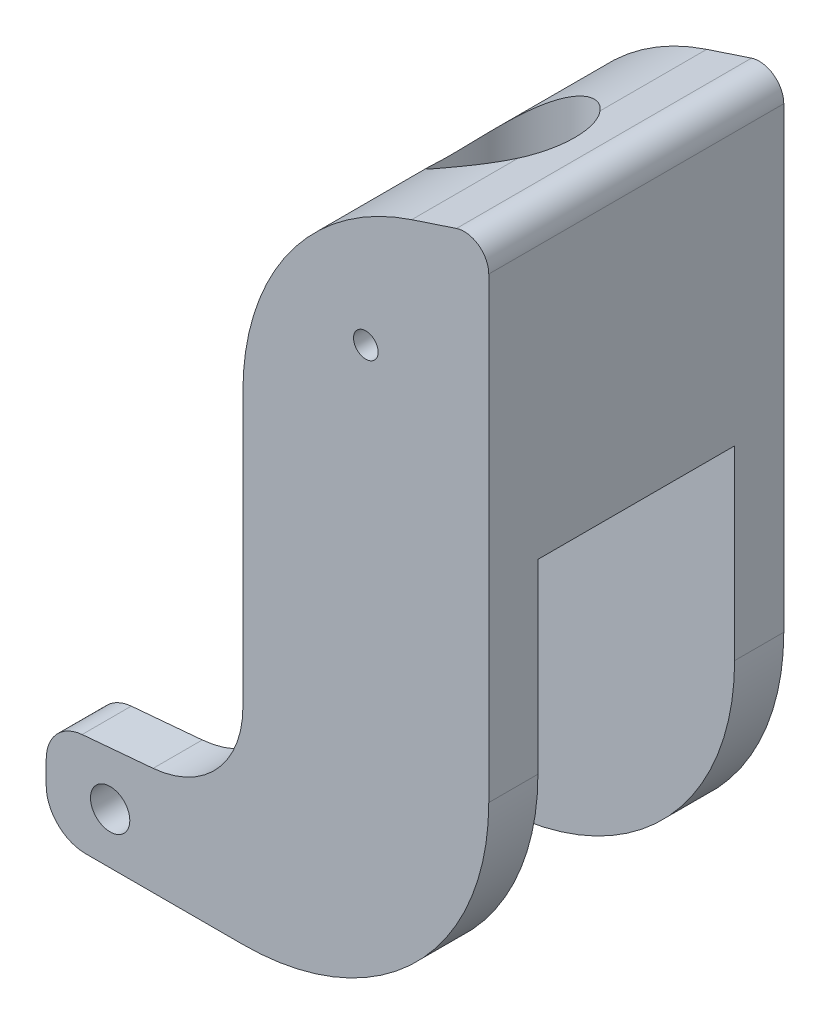
SolidWorks part; units mm, degrees
ref_plane "Front Plane" through (0, 0, 0) normal (0, 0, 1) x (1, 0, 0)
ref_plane "Top Plane" through (0, 0, 0) normal (0, 1, 0) x (1, 0, 0)
ref_plane "Right Plane" through (0, 0, 0) normal (1, 0, 0) x (0, 0, -1)
sketch "Sketch1" plane through (0, 0, 0) normal (0, 0, 1) x (1, 0, 0)
  line L0 (0, 18.3266) -> (0, 73.8482)
  line L1 (-18.2569, -1.5973) -> (-32.6972, -2.8606)
  line L2 (-40, -10.8302) -> (-40, -15.4995)
  line L3 (-32, -23.4995) -> (0, -23.4995)
  line L4 (50, 26.5005) -> (50, 119.5852)
  line L5 (43.4331, 124.3333) -> (34.3307, 121.3295)
  arc A0 (0, 73.8482) -> (34.3307, 121.3295) centre (50, 73.8482) cw
  arc A1 (0, -23.4995) -> (50, 26.5005) centre (0, 26.5005) ccw
  arc A2 (50, 119.5852) -> (43.4331, 124.3333) centre (45, 119.5852) ccw
  arc A3 (-32.6972, -2.8606) -> (-40, -10.8302) centre (-32, -10.8302) ccw
  arc A4 (-40, -15.4995) -> (-32, -23.4995) centre (-32, -15.4995) ccw
  arc A5 (0, 18.3266) -> (-18.2569, -1.5973) centre (-20, 18.3266) cw
  circle A6 centre (-27, -13.1649) radius 4
  point P9 (0, 110)
  point P12 (50, -23.4995)
  point P15 (50, 126.5005)
  point P18 (-40, -3.4995)
  point P21 (-40, -23.4995)
  point P24 (0, 0)
  point P27 (0, 0)
  point P28 (-40, -13.1649)
  dimension "D7" = 50
  dimension "D8" = 50
  dimension "D9" = 5
  dimension "D10" = 8
  dimension "D11" = 20
  dimension "D12" = 8
  dimension "D1" = 110
  dimension "D2" = 95
  dimension "D3" = 40
  dimension "D4" = 90
  dimension "D5" = 150
  dimension "D6" = 20
  dimension "D13" = 13
extrude "Boss-Extrude1" add sketch "Sketch1" along normal blind 60
sketch "Sketch2" plane through (0, 0, 0) normal (1, 0, 0) x (0, 0, -1)
  line L0 (-60, 124.3333) -> (0, 124.3333) construction
  line L1 (-10, -35.6667) -> (-50, -35.6667)
  line L2 (-10, -35.6667) -> (-10, 64.3333)
  line L3 (-10, 64.3333) -> (-50, 64.3333)
  line L4 (-50, -35.6667) -> (-50, 64.3333)
  line L5 (-10, -35.6667) -> (-50, 64.3333) construction
  line L6 (-10, 64.3333) -> (-50, -35.6667) construction
  line L7 (-60, 73.8482) -> (-60, 18.3266) construction
  line L8 (0, 73.8482) -> (0, 18.3266) construction
  point P0 (-30, 14.3333)
  point P5 (-30.3361, 21.4709)
  dimension "D1" = 60
  dimension "D2" = 10
  dimension "D3" = 10
  dimension "D4" = 100
extrude "Cut-Extrude1" cut sketch "Sketch2" against normal through all both and the other way through all
sketch "Sketch4" plane through (0, 0, 0) normal (0, 1, 0) x (1, 0, 0)
  line L0 (50, -60) -> (50, 0) construction
  line L1 (50, -60) -> (50, 0) construction
  circle A0 centre (25, -30) radius 12.5
  dimension "D2" = 25
  dimension "D1" = 25
  dimension "D3" = 30
extrude "Cut-Extrude2" cut sketch "Sketch4" against normal through all both and the other way through all
sketch "Sketch5" plane through (0, 0, 60) normal (0, 0, 1) x (1, 0, 0)
  line L6 (0, 73.8482) -> (0, 18.3266)
  line L7 (-18.2569, -1.5973) -> (-32.6972, -2.8606)
  line L8 (-40, -10.8302) -> (-40, -15.4995)
  line L9 (-32, -23.4995) -> (0, -23.4995)
  line L10 (50, 26.5005) -> (50, 119.5852)
  line L11 (43.4331, 124.3333) -> (34.3307, 121.3295)
  line L12 (0, 73.8482) -> (0, 18.3266) construction
  line L13 (-18.2569, -1.5973) -> (-32.6972, -2.8606) construction
  line L14 (-40, -10.8302) -> (-40, -15.4995) construction
  line L15 (-32, -23.4995) -> (0, -23.4995) construction
  line L16 (50, 26.5005) -> (50, 119.5852) construction
  line L17 (43.4331, 124.3333) -> (34.3307, 121.3295) construction
  circle A0 centre (25, 94.5852) radius 2.5
  arc A6 (34.3307, 121.3295) -> (0, 73.8482) centre (50, 73.8482) ccw
  arc A7 (-18.2569, -1.5973) -> (0, 18.3266) centre (-20, 18.3266) ccw
  arc A8 (-32.6972, -2.8606) -> (-40, -10.8302) centre (-32, -10.8302) ccw
  arc A9 (-40, -15.4995) -> (-32, -23.4995) centre (-32, -15.4995) ccw
  arc A10 (0, -23.4995) -> (50, 26.5005) centre (0, 26.5005) ccw
  arc A11 (50, 119.5852) -> (43.4331, 124.3333) centre (45, 119.5852) ccw
  arc A12 (34.3307, 121.3295) -> (0, 73.8482) centre (50, 73.8482) ccw construction
  arc A13 (-18.2569, -1.5973) -> (0, 18.3266) centre (-20, 18.3266) ccw construction
  arc A14 (-32.6972, -2.8606) -> (-40, -10.8302) centre (-32, -10.8302) ccw construction
  arc A15 (-40, -15.4995) -> (-32, -23.4995) centre (-32, -15.4995) ccw construction
  arc A16 (0, -23.4995) -> (50, 26.5005) centre (0, 26.5005) ccw construction
  arc A17 (50, 119.5852) -> (43.4331, 124.3333) centre (45, 119.5852) ccw construction
  dimension "D4" = 5
  dimension "D2" = 25
  dimension "D3" = 25
  dimension "D1" = 0
extrude "Cut-Extrude3" cut sketch "Sketch5" against normal through all both
